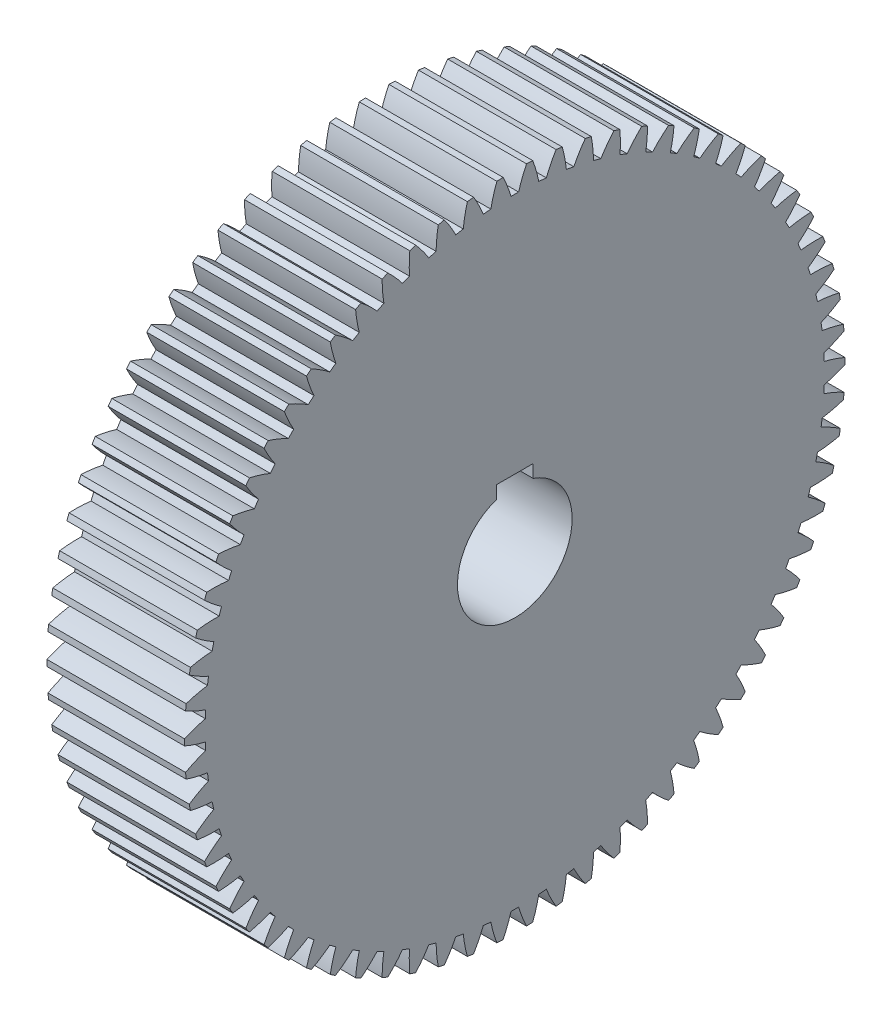
SolidWorks part; units mm, degrees
ref_plane "Plane1" through (0, 0, 0) normal (0, 0, 1) x (1, 0, 0)
ref_plane "Plane2" through (0, 0, 0) normal (0, 1, 0) x (1, 0, 0)
ref_plane "Plane3" through (0, 0, 0) normal (1, 0, 0) x (0, 0, -1)
sketch "HoldingSke" plane through (0, 0, 0) normal (0, 1, 0) x (1, 0, 0)
  line L0 (0, 0) -> (0.0855, -0.2349)
  line L1 (-15, 0) -> (100, 0) construction
  line L2 (0, 0) -> (-2.1039, 2.3779)
  line L3 (0, 0) -> (-11.863, 4.5341)
  line L4 (0, 0) -> (2.9537, 8.1152)
  line L5 (0, 0) -> (-46.8476, -17.4728)
  line L6 (0, 0) -> (-49.7378, -33.5582)
  line L7 (-2.1039, 2.3779) -> (10.8111, 60.9715)
  line L8 (-76.2, 54.61) -> (-71.9, 54.61)
  line L9 (-71.009, 38.7566) -> (-53.1078, 45.2721)
  line L10 (-76.2, 71.12) -> (104.1128, 71.12)
  line L11 (0, 0) -> (-60, 0)
  line L12 (-76.2, 101.6) -> (-76.073, 101.6)
  line L13 (24.9733, 27.94) -> (52.9518, 28.4284)
  line L14 (24.9733, 27.94) -> (24.9743, 27.94)
  line L15 (24.9733, 27.94) -> (100.4006, 29.5858)
  line L16 (-63.627, -4) -> (-12.827, -4)
  circle A0 centre (0, 0) radius 25
  circle A1 centre (0, 0) radius 37.5
  circle A2 centre (0, 0) radius 37.5
  circle A3 centre (0, 0) radius 25
  dimension "MHD" = 75
  dimension "Hub_dia" = 75
  dimension "Bore" = 50
  dimension "MBD" = 50
  dimension "Num_teeth" = 70
  dimension "Pitch" = 0.25
  dimension "Overall_len" = 50
  dimension "Show_teeth" = 70
  dimension "Thickness" = 60
  dimension "OAL" = 60.0001
  dimension "T_dim" = 4.3
  dimension "Ap" = 20
  dimension "H" = 19.05
  dimension "Pitch_radius" = 180.3128
  dimension "Width" = 60
  dimension "Backlash" = 0.127
  dimension "Addendum_fac" = 1
  dimension "Dedendum_fac" = 1.25
  dimension "Clearance_fac" = 0.25
  dimension "Dedendum_add" = 0.001
  dimension "Module" = 4
sketch "BasProSke" plane through (0, 0, 0) normal (0, 1, 0) x (1, 0, 0)
  line L0 (-10, 0) -> (60, 0) construction
  line L1 (0, 0) -> (0, 144)
  line L2 (0, 0) -> (60, 0)
  line L3 (60, 0) -> (60, 144)
  line L4 (60, 144) -> (0, 144)
  dimension "Thickness" = 60
  dimension "Diameter" = 288
revolve "Base-Revolve" add sketch "BasProSke" angle 360 about L0
sketch "TooCutSke" plane through (0, 0, 0) normal (1, 0, 0) x (0, 0, -1)
  line L1 (0, 0) -> (0, 107) construction
  line L2 (0, 0) -> (-3.3636, 139.9596) construction
  line L3 (0, 0) -> (-12.5594, 279.6572) construction
  line L4 (-3.3636, 139.9596) -> (-6.2797, 139.8286) construction
  arc A0 (1.6575, 134.9888) -> (-1.6575, 134.9888) centre (0, 0) ccw
  arc A1 (5.1214, 143.9343) -> (-5.1214, 143.9343) centre (0, 0) ccw
  circle A2 centre (0, 0) radius 140 construction
  circle A3 centre (0, 0) radius 131.557 construction
  arc A4 (-1.6575, 134.9888) -> (-5.1214, 143.9343) centre (-55.4191, 119.3145) ccw
  arc A5 (5.1214, 143.9343) -> (1.6575, 134.9888) centre (55.4191, 119.3145) ccw
  dimension "Root_dia" = 269.998
  dimension "Overcut_dia" = 288.0508
  dimension "Pitch_dia" = 280
  dimension "Base_dia" = 263.1139
  dimension "Flank_rad" = 56
  dimension "Half_ang" = 2.571
  dimension "Half_CT" = 2.9191
extrude "ToothCut" cut sketch "TooCutSke" along normal through all
fillet "Breaks" [suppressed] radius 0.08
fillet "RootFillets" [suppressed] radius 1.001
pattern_circular "TeethCuts" count 70 every 5.143 about axis through (-10, 0, 0) along (1, 0, 0) of "ToothCut", "RootFillets", "Breaks"
sketch "HubNeaOneSke" plane through (0, 0, 0) normal (-1, 0, 0) x (0, 0, 1)
  circle A0 centre (0, 0) radius 37.5
  dimension "Diameter" = 75
extrude "HubNearOne" [suppressed] add sketch "HubNeaOneSke" along normal blind 12.7001
sketch "HubNeaBotSke" plane through (0, 0, 0) normal (-1, 0, 0) x (0, 0, 1)
  circle A0 centre (0, 0) radius 37.5
  dimension "Diameter" = 75
extrude "HubNearBoth" [suppressed] add sketch "HubNeaBotSke" along normal blind 6.35
ref_plane "FarPln" through (60, 0, 0) normal (1, 0, 0) x (0, 0, -1)
sketch "HubFarSke" plane through (60, 0, 0) normal (1, 0, 0) x (0, 0, -1)
  circle A0 centre (0, 0) radius 37.5
  dimension "Diameter" = 75
extrude "HubFar" [suppressed] add sketch "HubFarSke" along normal blind 6.35
sketch "BorSke" plane through (0, 0, 0) normal (1, 0, 0) x (0, 0, -1)
  circle A0 centre (0, 0) radius 25
  dimension "Diameter" = 50
extrude "Bore" cut sketch "BorSke" along normal mid plane 120.0001
sketch "KeySke" plane through (0, 0, 0) normal (1, 0, 0) x (0, 0, -1)
  line L0 (-8, 0) -> (-8, 29.3)
  line L1 (-8, 29.3) -> (8, 29.3)
  line L2 (8, 29.3) -> (8, 0)
  line L3 (0, 0) -> (0, 34) construction
  line L4 (-8, 0) -> (8, 0)
  dimension "Offset" = 29.3
  dimension "Width" = 16
extrude "Keyway" cut sketch "KeySke" along normal mid plane 120.0001
pattern_circular "Keyway2" [suppressed] count 2 every 90 about axis through (-10, 0, 0) along (1, 0, 0)
equation "' \"Module@HoldingSke\" = 6.35"
equation "' \"Num_teeth@HoldingSke\" = 12"
equation "' \"Ap@HoldingSke\" =  20"
equation "' \"Ap@HoldingSke\" = 20"
equation "' \"Width@HoldingSke\" = 0.5 * 25.4"
equation "' \"Hub_dia@HoldingSke\"= 1 * 25.4"
equation "' \"Hub_dia@HoldingSke\" = 1 * 25.4"
equation "' \"Overall_len@HoldingSke\" = 1.0 * 25.4"
equation "' \"Bore@HoldingSke\" = 0.75 * 25.4"
equation "' \"T_dim@HoldingSke\" = 0.1 * 25.4"
equation "' \"Width@KeySke\" = 0.25 * 25.4"
equation "' \"Show_teeth@HoldingSke\" = 13"
equation "' \"Backlash@HoldingSke\" = 0.009 * 25.4"
equation "' \"Addendum_fac@HoldingSke\" = 1.0"
equation "' \"Dedendum_fac@HoldingSke\" = 1.25"
equation "' \"Dedendum_add@HoldingSke\" = 0.00005 * 25.4"
equation "' \"Clearance_fac@HoldingSke\" = 0.25"
equation "\"Pitch@HoldingSke\" = 1 / \"Module@HoldingSke\""
equation "\"Overcut_dia@TooCutSke\" = (\"Num_teeth@HoldingSke\" + 2 * \"Addendum_fac@HoldingSke\") / \"Pitch@HoldingSke\" + 0.002 * 25.4"
equation "\"Pitch_dia@TooCutSke\" = \"Num_teeth@HoldingSke\" / \"Pitch@HoldingSke\""
equation "\"Base_dia@TooCutSke\" = \"Num_teeth@HoldingSke\" / \"Pitch@HoldingSke\" * cos((\"Ap@HoldingSke\"  * 3.14159265 / 180))"
equation "\"Root_dia@TooCutSke\" = (\"Num_teeth@HoldingSke\" + 2) / \"Pitch@HoldingSke\" - 2 * (\"Addendum_fac@HoldingSke\" + \"Dedendum_fac@HoldingSke\") / \"Pitch@HoldingSke\" - \"Dedendum_add@HoldingSke\" * 2"
equation "\"Half_ang@TooCutSke\" = 180 / \"Num_teeth@HoldingSke\""
equation "\"Half_CT@TooCutSke\" = \"Num_teeth@HoldingSke\" / \"Pitch@HoldingSke\" * sin((3.14159265 / 2 / \"Num_teeth@HoldingSke\")) / 2 - 7 * \"Backlash@HoldingSke\" / 4"
equation "\"Flank_rad@TooCutSke\" = \"Num_teeth@HoldingSke\" / \"Pitch@HoldingSke\" / 5"
equation "\"Radius@RootFillets\" = \"Clearance_fac@HoldingSke\" / \"Pitch@HoldingSke\" + \"Dedendum_add@HoldingSke\""
equation "\"Break_rad@Breaks\" = 0.02 / \"Pitch@HoldingSke\""
equation "\"Thickness@HoldingSke\" = \"Width@HoldingSke\""
equation "\"OAL@HoldingSke\" = \"Thickness@HoldingSke\""
equation "\"MHD@HoldingSke\" = (\"Num_teeth@HoldingSke\" + 2) / \"Pitch@HoldingSke\" - 2 * (\"Addendum_fac@HoldingSke\" + \"Dedendum_fac@HoldingSke\")  / \"Pitch@HoldingSke\" - \"Dedendum_add@HoldingSke\" * 2"
equation "\"MBD@HoldingSke\" = (\"Num_teeth@HoldingSke\" + 2) / \"Pitch@HoldingSke\" - 2 * (\"Addendum_fac@HoldingSke\" + \"Dedendum_fac@HoldingSke\")  / \"Pitch@HoldingSke\" - \"Dedendum_add@HoldingSke\" * 2 - 0.002 * 25.4"
equation "\"MHD@HoldingSke\" = ((sgn( \"MHD@HoldingSke\" - \"Hub_dia@HoldingSke\" )-1)*( \"MHD@HoldingSke\" - \"Hub_dia@HoldingSke\" ))/-2+ \"Hub_dia@HoldingSke\""
equation "\"MBD@HoldingSke\" = ((sgn( \"MBD@HoldingSke\" - \"Bore@HoldingSke\" )-1)*( \"MBD@HoldingSke\" - \"Bore@HoldingSke\" ))/-2+ \"Bore@HoldingSke\""
equation "\"OAL@HoldingSke\" = ((sgn( \"OAL@HoldingSke\" - \"Overall_len@HoldingSke\" )+1)*( \"OAL@HoldingSke\" - \"Overall_len@HoldingSke\" ))/2 + \"Overall_len@HoldingSke\" + 0.000002 * 25.4"
equation "\"Num_teeth@TeethCuts\" = int( \"Show_teeth@HoldingSke\" ) + 1"
equation "\"Num_teeth@TeethCuts\" = ((sgn( \"Num_teeth@TeethCuts\" - \"Num_teeth@HoldingSke\" )-1)*( \"Num_teeth@TeethCuts\" - \"Num_teeth@HoldingSke\" ))/-2+ \"Num_teeth@HoldingSke\""
equation "\"Num_teeth@TeethCuts\" = ((sgn( \"Num_teeth@TeethCuts\" - 2.0)+1)*( \"Num_teeth@TeethCuts\" - 2.0))/2 +2.0"
equation "\"Angle@TeethCuts\" = 360.0 / \"Num_teeth@HoldingSke\""
equation "\"Diameter@BasProSke\" = (\"Num_teeth@HoldingSke\" + 2 * \"Addendum_fac@HoldingSke\") / \"Pitch@HoldingSke\""
equation "\"Thickness@BasProSke\"  = \"Thickness@HoldingSke\""
equation "' \"Fillet_rad@BasProSke\" =  \"Thickness@HoldingSke\" * 0.05"
equation "' \"Fillet_rad@BasProSke\" = \"Thickness@HoldingSke\" * 0.05"
equation "\"MHD@HoldingSke\" = ((sgn( \"MHD@HoldingSke\" - \"Root_dia@TooCutSke\" )-1)*( \"MHD@HoldingSke\" - \"Root_dia@TooCutSke\" ))/-2+ \"Root_dia@TooCutSke\""
equation "\"Diameter@HubNeaOneSke\" = \"MHD@HoldingSke\""
equation "\"Length@HubNearOne\" = \"OAL@HoldingSke\" - \"Thickness@BasProSke\""
equation "\"Diameter@HubNeaBotSke\" = \"MHD@HoldingSke\""
equation "\"Length@HubNearBoth\" = ( \"OAL@HoldingSke\" - \"Thickness@BasProSke\" ) / 2.0"
equation "\"Thickness@FarPln\" = \"Thickness@BasProSke\""
equation "\"Diameter@HubFarSke\" = \"MHD@HoldingSke\""
equation "\"Length@HubFar\" = ( \"OAL@HoldingSke\" - \"Thickness@BasProSke\" ) / 2.0"
equation "\"Diameter@BorSke\" = \"MBD@HoldingSke\""
equation "\"D1@Bore\" = \"OAL@HoldingSke\" * 2.0"
equation "\"D1@Keyway\" = \"OAL@HoldingSke\" * 2.0"
equation "\"Offset@KeySke\" = \"T_dim@HoldingSke\" + \"MBD@HoldingSke\" / 2.0"
